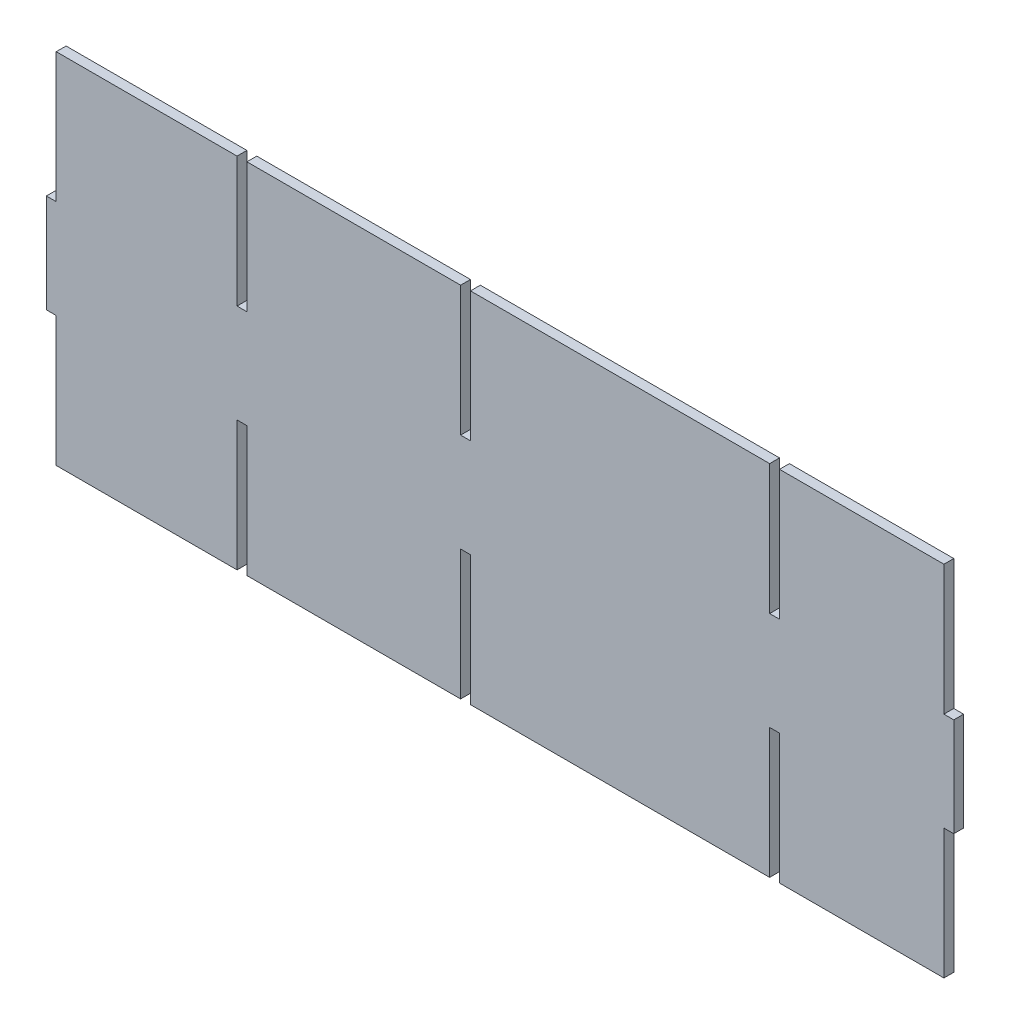
SolidWorks part; units mm, degrees
ref_plane "Front Plane" through (0, 0, 0) normal (0, 0, 1) x (1, 0, 0)
ref_plane "Top Plane" through (0, 0, 0) normal (0, 1, 0) x (1, 0, 0)
ref_plane "Right Plane" through (0, 0, 0) normal (1, 0, 0) x (0, 0, -1)
sketch "Sketch1" plane through (0, 0, 0) normal (0, 0, 1) x (1, 0, 0)
  line L0 (0, 0) -> (3, 0)
  line L1 (3, 0) -> (3, -39.5)
  line L2 (3, -39.5) -> (58, -39.5)
  line L3 (58, -39.5) -> (58, 0)
  line L4 (58, 0) -> (61, 0)
  line L5 (61, 0) -> (61, -39.5)
  line L6 (61, -39.5) -> (126, -39.5)
  line L7 (126, -39.5) -> (126, 0)
  line L8 (126, 0) -> (129, 0)
  line L9 (129, 0) -> (129, -39.5)
  line L10 (129, -39.5) -> (220, -39.5)
  line L11 (220, -39.5) -> (220, 0)
  line L12 (220, 0) -> (223, 0)
  line L13 (223, 0) -> (223, -39.5)
  line L14 (223, -39.5) -> (273, -39.5)
  line L15 (273, -39.5) -> (273, 0)
  line L16 (273, 0) -> (276, 0)
  line L17 (276, 0) -> (276, 30)
  line L18 (276, 15) -> (0, 15) construction
  line L19 (0, 30) -> (0, 0)
  line L20 (273, 30) -> (276, 30)
  line L21 (273, 69.5) -> (273, 30)
  line L22 (223, 69.5) -> (273, 69.5)
  line L23 (223, 30) -> (223, 69.5)
  line L24 (220, 30) -> (223, 30)
  line L25 (220, 69.5) -> (220, 30)
  line L26 (129, 69.5) -> (220, 69.5)
  line L27 (129, 30) -> (129, 69.5)
  line L28 (126, 30) -> (129, 30)
  line L29 (126, 69.5) -> (126, 30)
  line L30 (61, 69.5) -> (126, 69.5)
  line L31 (61, 30) -> (61, 69.5)
  line L32 (58, 30) -> (61, 30)
  line L33 (58, 69.5) -> (58, 30)
  line L34 (3, 69.5) -> (58, 69.5)
  line L35 (3, 30) -> (3, 69.5)
  line L36 (0, 30) -> (3, 30)
  dimension "D1" = 15
  dimension "D2" = 54.5
  dimension "D3" = 3
  dimension "D4" = 3
  dimension "D5" = 3
  dimension "D6" = 3
  dimension "D7" = 15
  dimension "D8" = 3
  dimension "D9" = 55
  dimension "D10" = 65
  dimension "D11" = 91
  dimension "D12" = 50
extrude "Boss-Extrude1" add sketch "Sketch1" along normal blind 3
